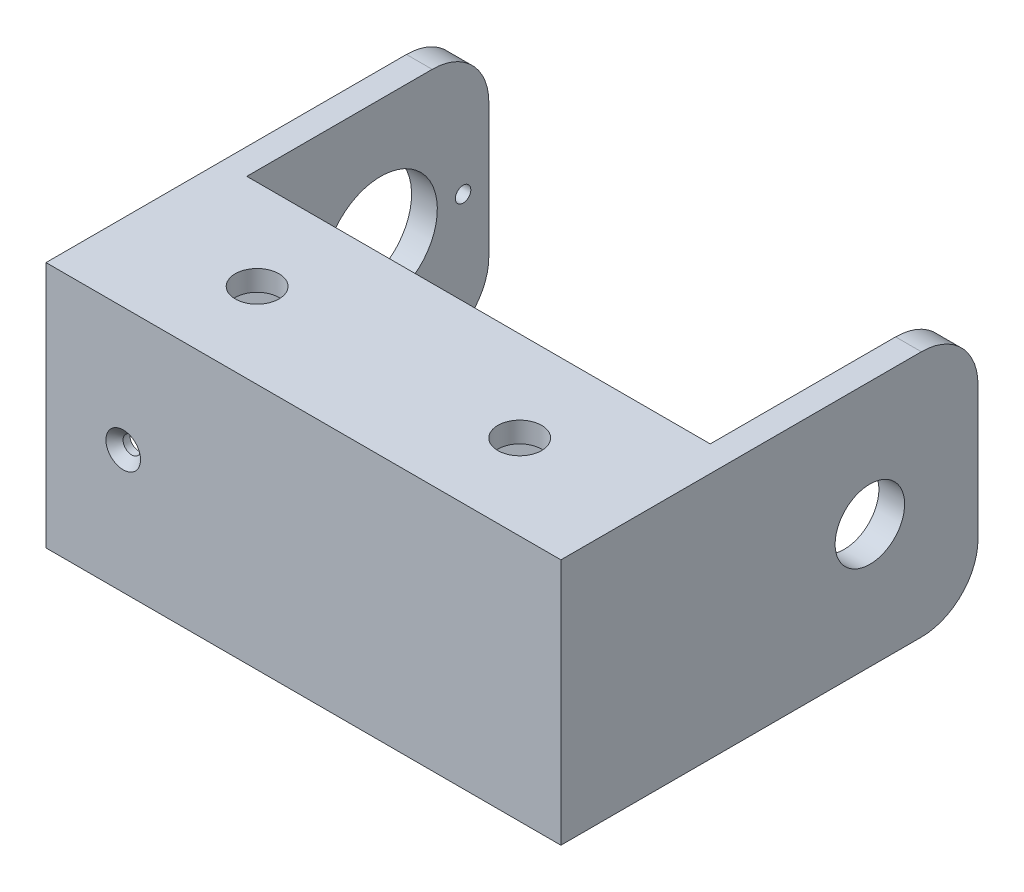
SolidWorks part; units mm, degrees
material "PVC 0.007 Plasticizado"
ref_plane "Plano frontal" through (0, 0, 0) normal (1, 0, 0) x (0, 1, 0)
ref_plane "Plano superior" through (0, 0, 0) normal (0, 0, 1) x (0, 1, 0)
ref_plane "Plano direito" through (0, 0, 0) normal (0, 1, 0) x (-1, 0, 0)
sketch "Esboço1" plane through (0, 0, 0) normal (0, 0, 1) x (0, 1, 0)
  line L1 (-24, -60) -> (24, -60)
  line L2 (-24, -60) -> (-24, 60)
  line L3 (-24, 60) -> (24, 60)
  line L4 (24, -60) -> (24, 60)
  line L5 (-24, -60) -> (24, 60) construction
  line L6 (-24, 60) -> (24, -60) construction
  point P0 (0, 0)
  dimension "D1" = 48
  dimension "D2" = 120
extrude "Ressalto-extrusão1" add sketch "Esboço1" along normal blind 3
sketch "Esboço2" plane through (0, 0, 0) normal (0, 0, -1) x (1, 0, 0)
  line L1 (-60, -24) -> (60, -24)
  line L2 (-60, -24) -> (-60, 24)
  line L3 (-60, 24) -> (60, 24)
  line L4 (60, -24) -> (60, 24)
  line L5 (-60, -24) -> (60, 24) construction
  line L6 (-60, 24) -> (60, -24) construction
  line L7 (-60, 20) -> (56, 20)
  line L8 (-60, 20) -> (-60, -20)
  line L9 (-60, -20) -> (56, -20)
  line L10 (56, 20) -> (56, -20)
  point P0 (0, 0)
  line M8 (-60, -24) -> (60, -24)
  line M9 (60, -24) -> (60, 24)
  line M10 (60, 24) -> (-60, 24)
  line M11 (-60, 24) -> (-60, -24)
  dimension "D1" = 4
  dimension "D2" = 4
  dimension "D3" = 4
extrude "Ressalto-extrusão2" add sketch "Esboço2" along normal blind 28 contours L7 L10 L9 M11 M8 M9 M10
sketch "Esboço3" plane through (0, 0, -28) normal (0, 0, -1) x (1, 0, 0)
  line L1 (-60, -24) -> (60, -24)
  line L2 (-60, -24) -> (-60, 24)
  line L3 (-60, 24) -> (60, 24)
  line L4 (60, -24) -> (60, 24)
  line L5 (-60, -24) -> (60, 24) construction
  line L6 (-60, 24) -> (60, -24) construction
  point P0 (0, 0)
extrude "Ressalto-extrusão3" add sketch "Esboço3" along normal blind 3
sketch "Esboço4" plane through (0, 0, -31) normal (0, 0, -1) x (1, 0, 0)
  line L0 (60, 24) -> (-60, 24) construction
  line L1 (-40, 24) -> (-35, 24)
  line L2 (-40, 24) -> (-40, -24)
  line L3 (-40, -24) -> (-35, -24)
  line L4 (-35, 24) -> (-35, -24)
  line L5 (-60, -24) -> (60, -24) construction
  line L6 (-60, 24) -> (-60, -24) construction
  line L8 (60, 24) -> (55, 24)
  line L9 (60, 24) -> (60, -24)
  line L10 (60, -24) -> (55, -24)
  line L11 (55, 24) -> (55, -24)
  dimension "D1" = 5
  dimension "D2" = 20
  dimension "D3" = 5
extrude "Ressalto-extrusão4" add sketch "Esboço4" along normal blind 47
sketch "Esboço5" plane through (-40, 0, 0) normal (-1, 0, 0) x (0, -1, 0)
  line L0 (24, -31) -> (-24, -31) construction
  circle A0 centre (0, -57) radius 11
  dimension "D1" = 22
  dimension "D2" = 26
extrude "Corte-extrusão1" cut sketch "Esboço5" against normal up to surface (5 mm away) up to face at (-35, 0, -54.5)
sketch "Esboço6" plane through (0, -24, 0) normal (0, -1, 0) x (1, 0, 0)
  line L0 (-15.5, -13.5) -> (35.5, -13.5) construction
  line L1 (-60, 3) -> (60, 3) construction
  line L2 (60, 3) -> (60, -78) construction
  line L3 (-35, -78) -> (-35, -31) construction
  circle A0 centre (-15.5, -13.5) radius 4.25
  circle A1 centre (35.5, -13.5) radius 4.25
  dimension "D1" = 8.5
  dimension "D2" = 8.5
  dimension "D3" = 16.5
  dimension "D4" = 24.5
  dimension "D5" = 19.5
extrude "Corte-extrusão2" cut sketch "Esboço6" against normal through all
fillet "Filete1" radius 11 4 edges at (57.5, 24, -78) (57.5, -24, -78) (-37.5, -24, -78) (-37.5, 24, -78)
sketch "Esboço7" plane through (55, 0, 0) normal (-1, 0, 0) x (0, -1, 0)
  circle A0 centre (0, -57) radius 6.75
  dimension "D1" = 13.5
extrude "Corte-extrusão3" cut sketch "Esboço7" against normal through all
sketch "Esboço8" plane through (0, 0, -31) normal (0, 0, -1) x (1, 0, 0)
  line L0 (-60, 24) -> (-60, -24) construction
  line L1 (-60, -24) -> (-40, -24)
  line L2 (-60, -24) -> (-60, 24)
  line L3 (-60, 24) -> (-40, 24)
  line L4 (-40, -24) -> (-40, 24)
  line L5 (-40, 24) -> (-40, -24) construction
  line L8 (-60, -24) -> (-40, -24) construction
  line L9 (-40, 24) -> (-60, 24) construction
extrude "Corte-extrusão4" cut sketch "Esboço8" against normal through all
sketch "Esboço12" plane through (0, 0, 3) normal (0, 0, 1) x (1, 0, 0)
  line L0 (60, -24) -> (60, 24) construction
  circle A0 centre (-25, 0) radius 1.5
  dimension "D2" = 3
  dimension "D1" = 85
extrude "Corte-extrusão5" cut sketch "Esboço12" against normal up to surface (3 mm away) up to face at (8, 0, 0)
hole_wizard "Escareado para SFHCS M31" positions "Esboço15" profile "Esboço16" countersink size "M3" standard "Ansi Metric"
sketch "Esboço15" plane through (0, 0, 3) normal (0, 0, 1) x (0, -1, 0)
  point P0 (0, -25)
sketch "Esboço16" plane through (-25, 0, 3) normal (1, 0, 0) x (0, -1, 0)
  line L0 (0, 0) -> (0, 4.0215)
  line L1 (0, 4.0215) -> (1.7, 3)
  line L2 (1.7, 3) -> (1.7, 1.66)
  line L3 (1.7, 1.66) -> (3.36, 0)
  line L5 (3.36, 0) -> (0, 0)
  line L6 (-1.7, 1.66) -> (-3.36, 0) construction
  line L10 (0, 4.0215) -> (-1.7, 3) construction
  line L11 (0, -6.35) -> (0, 107.95) construction
  dimension "Hole Dia." = 3.4
  dimension "Hole Depth" = 3
  dimension "Near C'Sink Dia." = 6.72
  dimension "Near C'Sink Angle" = 90
  dimension "Drill Angle" = 118
sketch "Esboço18" plane through (-40, 0, 0) normal (-1, 0, 0) x (0, -1, 0)
  line L0 (-24, -67) -> (-24, 3) construction
  line L1 (24, -67) -> (24, 3) construction
  line L2 (20, -28) -> (-20, -28) construction
  line L3 (13, -78) -> (-13, -78) construction
  line L5 (0, 0) -> (0, -78) construction
  circle A0 centre (-16, -33) radius 1.5
  circle A1 centre (16, -33) radius 1.5
  circle A2 centre (0, -73) radius 1.5
  dimension "D1" = 3
  dimension "D2" = 3
  dimension "D3" = 3
  dimension "D4" = 8
  dimension "D5" = 8
  dimension "D6" = 5
  dimension "D7" = 5
extrude "Corte-extrusão6" cut sketch "Esboço18" against normal up to surface (5 mm away) up to face at (-35, -11, -57)
